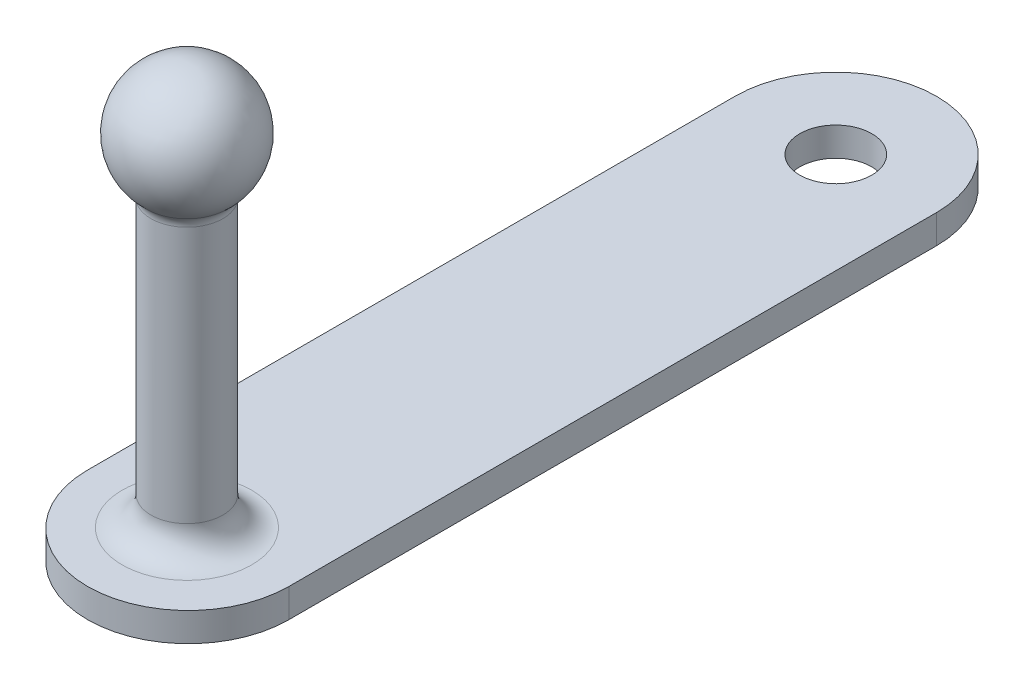
SolidWorks part; units mm, degrees
ref_plane "Front Plane" through (0, 0, 0) normal (0, 0, 1) x (1, 0, 0)
ref_plane "Top Plane" through (0, 0, 0) normal (0, 1, 0) x (1, 0, 0)
ref_plane "Right Plane" through (0, 0, 0) normal (1, 0, 0) x (0, 0, -1)
sketch "Sketch3" plane through (0, 0, 0) normal (0, 0, 1) x (1, 0, 0)
  line L0 (0, 0) -> (0, 22.3131)
  line L1 (0, 0) -> (2.5, 0)
  line L2 (2.5, 0) -> (2.5, 30)
  arc A0 (2.5, 30) -> (0, 22.3131) centre (2.5, 25.75) ccw
  dimension "D3" = 4.25
  dimension "D1" = 30
  dimension "D2" = 2.5
revolve "Revolve1" add sketch "Sketch3" angle 360 about L2
sketch "Sketch4" plane through (0, 0, 0) normal (0, -1, 0) x (1, 0, 0)
  line L0 (2.5892, 0) -> (2.5892, -45) construction
  line L1 (9.5892, 0) -> (9.5892, -45)
  line L2 (-4.4108, 0) -> (-4.4108, -45)
  arc A0 (9.5892, 0) -> (-4.4108, 0) centre (2.5892, 0) ccw
  arc A1 (-4.4108, -45) -> (9.5892, -45) centre (2.5892, -45) ccw
  circle A2 centre (2.5892, -45) radius 2.5
  point P2 (2.5892, -22.5)
  dimension "D2" = 7
  dimension "D4" = 5
  dimension "D1" = 45
  dimension "D3" = 0
extrude "Boss-Extrude1" add sketch "Sketch4" against normal blind 2
fillet "Fillet1" radius 2 1 edges at (2.5, 2, -2.5)
fillet "Fillet2" radius 1 1 edges at (2.5, 22.3131, -2.5)
